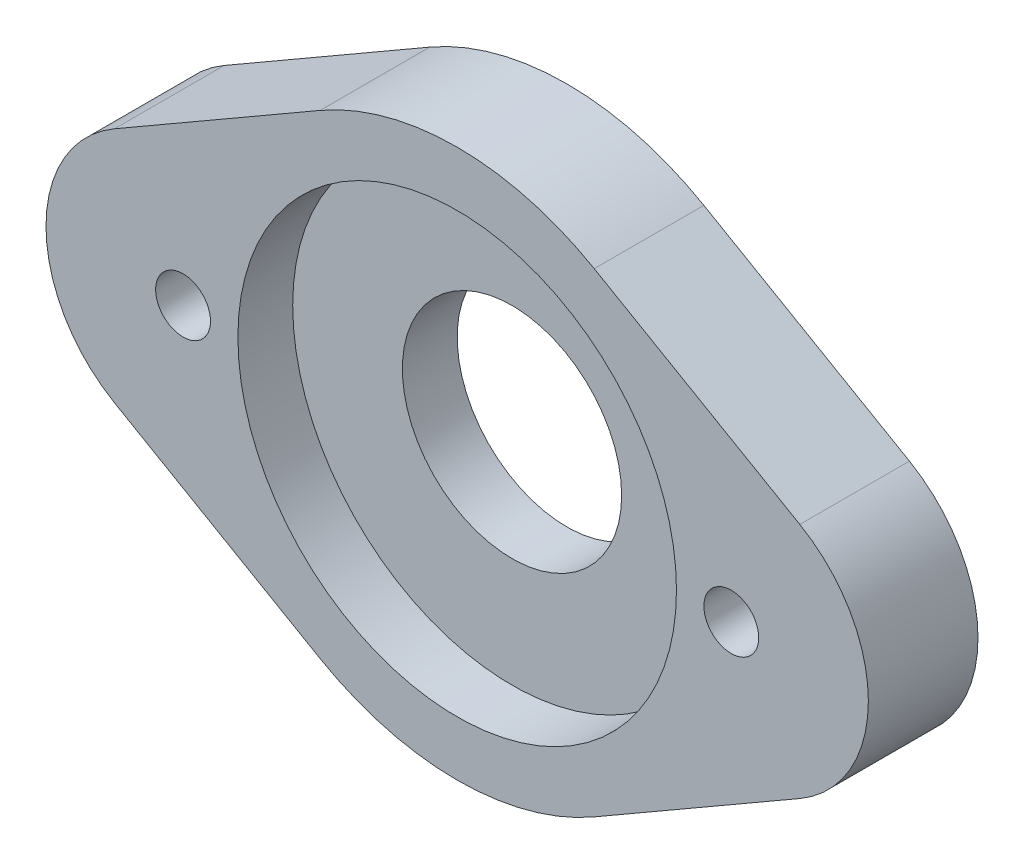
SolidWorks part; units mm, degrees
material "45钢"
ref_plane "前视基准面" through (0, 0, 0) normal (0, 0, 1) x (1, 0, 0)
ref_plane "上视基准面" through (0, 0, 0) normal (0, 1, 0) x (1, 0, 0)
ref_plane "右视基准面" through (0, 0, 0) normal (1, 0, 0) x (0, 0, -1)
sketch "草图1" plane through (0, 0, 0) normal (0, 0, 1) x (1, 0, 0)
  line L0 (55, 0) -> (-55, 0) construction
  line L1 (12.5, 21.6506) -> (31.25, 10.8253)
  line L2 (0, 0) -> (59.2519, 0) construction
  line L3 (12.5, -21.6506) -> (31.25, -10.8253)
  line L4 (0, 0) -> (0, 13.3197) construction
  line L5 (0, -55) -> (0, 55) construction
  line L6 (-12.5, -21.6506) -> (-31.25, -10.8253)
  line L7 (-12.5, 21.6506) -> (-31.25, 10.8253)
  arc A0 (-12.5, -21.6506) -> (12.5, -21.6506) centre (0, 0) ccw
  arc A1 (31.25, -10.8253) -> (31.25, 10.8253) centre (25, 0) ccw
  arc A2 (-31.25, -10.8253) -> (-31.25, 10.8253) centre (-25, 0) cw
  arc A3 (12.5, 21.6506) -> (-12.5, 21.6506) centre (0, 0) ccw
  point P13 (0, 13.3197)
  dimension "D1" = 50
  dimension "D2" = 25
  dimension "D3" = 25
extrude "凸台-拉伸1" add sketch "草图1" along normal blind 10
sketch "草图2" plane through (0, 0, 10) normal (0, 0, 1) x (1, 0, 0)
  circle A0 centre (0, 0) radius 20
  dimension "D1" = 40
extrude "切除-拉伸1" cut sketch "草图2" against normal blind 5
sketch "草图3" plane through (0, 0, 5) normal (0, 0, 1) x (1, 0, 0)
  circle A0 centre (0, 0) radius 10
  dimension "D1" = 20
extrude "切除-拉伸2" cut sketch "草图3" against normal up to next
sketch "草图4" plane through (0, 0, 10) normal (0, 0, 1) x (1, 0, 0)
  circle A0 centre (-25, 0) radius 2.5
  dimension "D1" = 5
extrude "切除-拉伸3" cut sketch "草图4" against normal up to next
mirror "镜向1" about plane through (0, 0, 0) normal (1, 0, 0) of "切除-拉伸3"
